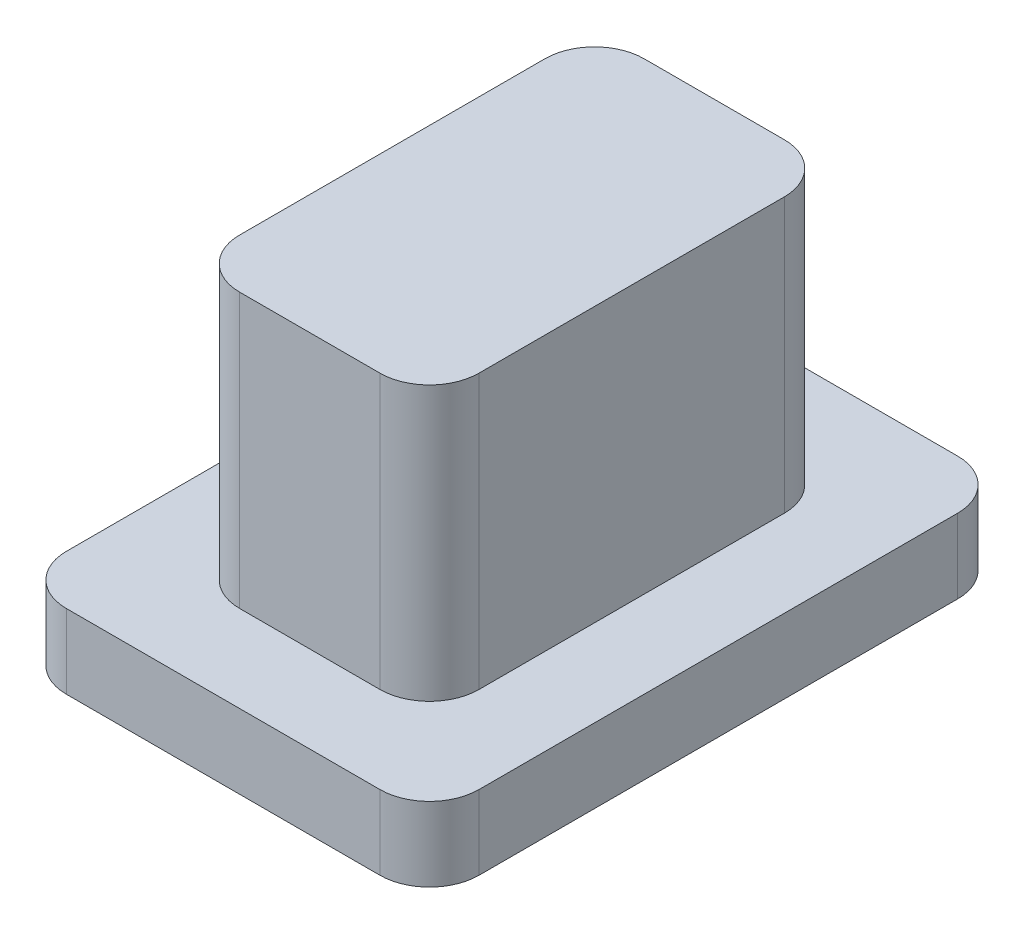
SolidWorks part; units mm, degrees
ref_plane "前视基准面" through (0, 0, 0) normal (0, 0, 1) x (1, 0, 0)
ref_plane "上视基准面" through (0, 0, 0) normal (0, 1, 0) x (1, 0, 0)
ref_plane "右视基准面" through (0, 0, 0) normal (1, 0, 0) x (0, 0, -1)
sketch "草图1" plane through (0, 0, 0) normal (0, 1, 0) x (1, 0, 0)
  line L1 (-2.5, 3.5) -> (2.5, 3.5)
  line L2 (-2.5, 3.5) -> (-2.5, -3.5)
  line L3 (-2.5, -3.5) -> (2.5, -3.5)
  line L4 (2.5, 3.5) -> (2.5, -3.5)
  line L5 (-2.5, 3.5) -> (2.5, -3.5) construction
  line L6 (-2.5, -3.5) -> (2.5, 3.5) construction
  point P0 (0, 0)
  dimension "D1" = 5
  dimension "D2" = 7
extrude "凸台-拉伸1" add sketch "草图1" along normal blind 0.9
sketch "草图2" plane through (0, 0.9, 0) normal (0, 1, 0) x (1, 0, 0)
  line L1 (-1.45, 2.45) -> (1.45, 2.45)
  line L2 (-1.45, 2.45) -> (-1.45, -2.45)
  line L3 (-1.45, -2.45) -> (1.45, -2.45)
  line L4 (1.45, 2.45) -> (1.45, -2.45)
  line L5 (-1.45, 2.45) -> (1.45, -2.45) construction
  line L6 (-1.45, -2.45) -> (1.45, 2.45) construction
  point P0 (0, 0)
  dimension "D1" = 2.9
  dimension "D2" = 4.9
extrude "凸台-拉伸2" add sketch "草图2" along normal blind 3.32
fillet "圆角1" radius 0.6 8 edges at (-1.45, 2.56, -2.45) (1.45, 2.56, -2.45) (1.45, 2.56, 2.45) (-1.45, 2.56, 2.45) (2.5, 0.45, -3.5) (-2.5, 0.45, -3.5) (2.5, 0.45, 3.5) (-2.5, 0.45, 3.5)
